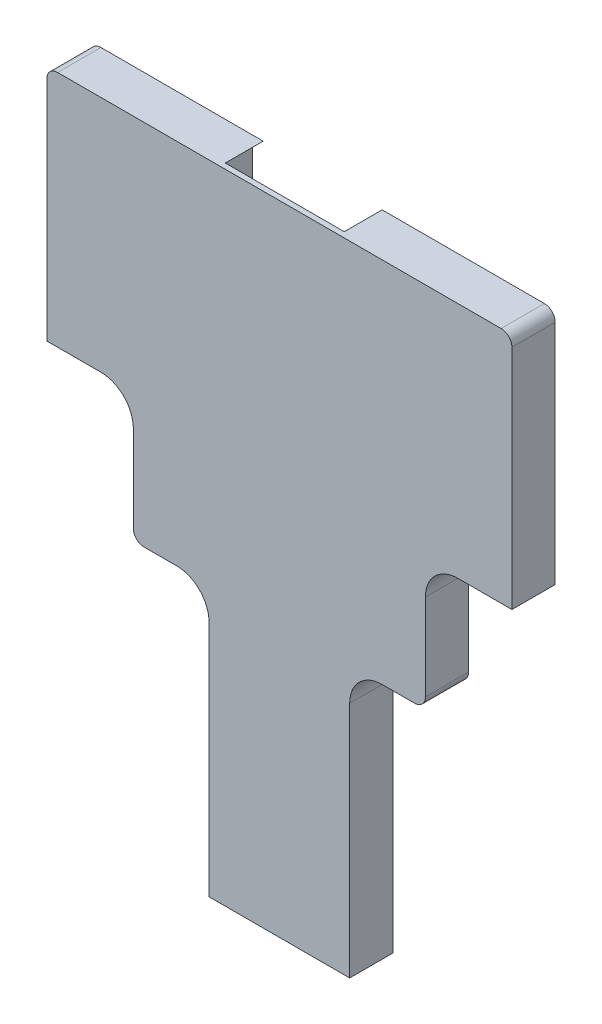
SolidWorks part; units mm, degrees
material "ABS"
ref_plane "Front Plane" through (0, 0, 0) normal (0, 0, 1) x (1, 0, 0)
ref_plane "Top Plane" through (0, 0, 0) normal (0, 1, 0) x (1, 0, 0)
ref_plane "Right Plane" through (0, 0, 0) normal (1, 0, 0) x (0, 0, -1)
sketch "Sketch3" plane through (0, 0, 0) normal (1, 0, 0) x (0, 0, -1)
  line L0 (0, 0) -> (4, 0)
  dimension "D1" = 4
ref_plane "Plane2" through (0, 0, -4) normal (0, 0, -1) x (-1, 0, 0)
sketch "Sketch4" plane through (0, 0, -4) normal (0, 0, -1) x (-1, 0, 0)
  line L0 (-6.5, 0) -> (6.5, 0)
  line L1 (6.5, 0) -> (6.5, 22)
  line L4 (16.5, 37) -> (21.5, 37)
  line L5 (21.5, 37) -> (21.5, 58)
  line L6 (20.5, 59) -> (-20.5, 59)
  line L8 (0, 59) -> (0, 0) construction
  line L9 (-6.5, 0) -> (-6.5, 22)
  line L12 (-16.5, 37) -> (-21.5, 37)
  line L13 (-21.5, 37) -> (-21.5, 58)
  line L15 (-13.5, 34) -> (-13.5, 26)
  line L16 (-12.5, 25) -> (-9.5, 25)
  line L17 (13.5, 34) -> (13.5, 26)
  line L18 (12.5, 25) -> (9.5, 25)
  arc A0 (9.5, 25) -> (6.5, 22) centre (9.5, 22) ccw
  arc A1 (16.5, 37) -> (13.5, 34) centre (16.5, 34) ccw
  arc A2 (-9.5, 25) -> (-6.5, 22) centre (-9.5, 22) cw
  arc A3 (-16.5, 37) -> (-13.5, 34) centre (-16.5, 34) cw
  arc A4 (-13.5, 26) -> (-12.5, 25) centre (-12.5, 26) ccw
  arc A5 (13.5, 26) -> (12.5, 25) centre (12.5, 26) cw
  arc A6 (-20.5, 59) -> (-21.5, 58) centre (-20.5, 58) ccw
  arc A7 (20.5, 59) -> (21.5, 58) centre (20.5, 58) cw
  point P17 (6.5, 25)
  point P20 (13.5, 37)
  point P23 (-6.5, 25)
  point P26 (-13.5, 37)
  point P33 (-21.5, 59)
  point P36 (21.5, 59)
  dimension "D3" = 3
  dimension "D4" = 3
  dimension "D7" = 3
  dimension "D8" = 3
  dimension "D9" = 1
  dimension "D10" = 1
  dimension "D5" = 1
  dimension "D1" = 6.5
  dimension "D2" = 25
  dimension "D6" = 8
sweep "Sweep1" add profiles "Sketch4" path "Sketch3"
sketch "Sketch5" plane through (0, 0, -4) normal (0, 0, -1) x (-1, 0, 0)
  line L0 (0, 0) -> (0, 59) construction
  line L1 (-6.5, 0) -> (6.5, 0) construction
  line L2 (20.5, 59) -> (-20.5, 59) construction
  line L3 (-1, 0) -> (1, 0)
  line L4 (1.5, 0.5) -> (1.5, 20)
  line L5 (1.5, 20) -> (2.5, 20)
  line L6 (3.5, 21) -> (3.5, 26)
  line L7 (4.5, 27) -> (5.5, 27)
  line L8 (6.5, 28) -> (6.5, 58)
  line L9 (5.5, 59) -> (-5.5, 59)
  line L11 (-6.5, 28) -> (-6.5, 58)
  line L12 (-4.5, 27) -> (-5.5, 27)
  line L13 (-3.5, 21) -> (-3.5, 26)
  line L14 (-1.5, 20) -> (-2.5, 20)
  line L15 (-1.5, 0.5) -> (-1.5, 20)
  arc A0 (-5.5, 59) -> (-6.5, 58) centre (-5.5, 58) ccw
  arc A1 (5.5, 59) -> (6.5, 58) centre (5.5, 58) cw
  arc A2 (6.5, 28) -> (5.5, 27) centre (5.5, 28) cw
  arc A3 (-6.5, 28) -> (-5.5, 27) centre (-5.5, 28) ccw
  arc A4 (-3.5, 21) -> (-2.5, 20) centre (-2.5, 21) ccw
  arc A5 (3.5, 21) -> (2.5, 20) centre (2.5, 21) cw
  arc A6 (-4.5, 27) -> (-3.5, 26) centre (-4.5, 26) cw
  arc A7 (4.5, 27) -> (3.5, 26) centre (4.5, 26) ccw
  arc A8 (-1, 0) -> (-1.5, 0.5) centre (-1, 0.5) cw
  arc A9 (1, 0) -> (1.5, 0.5) centre (1, 0.5) ccw
  point P22 (6.5, 59)
  point P25 (6.5, 27)
  point P32 (3.5, 20)
  point P37 (3.5, 27)
  point P42 (1.5, 0)
  dimension "D8" = 1
  dimension "D9" = 1
  dimension "D10" = 1
  dimension "D11" = 1
  dimension "D12" = 1
  dimension "D13" = 1
  dimension "D14" = 1
  dimension "D15" = 0.5
  dimension "D16" = 0.5
  dimension "D1" = 1.5
  dimension "D2" = 20
  dimension "D3" = 2
  dimension "D4" = 7
  dimension "D5" = 3
  dimension "D6" = 32
  dimension "D7" = 6.5
extrude "Cut-Extrude1" cut sketch "Sketch5" against normal blind 3.5 contours L9 A0 L11 A3 L12 A6 L13 A4 L14 L15 A8 L3 A9 L4 L5 A5 L6 A7 L7 A2 L8 A1
